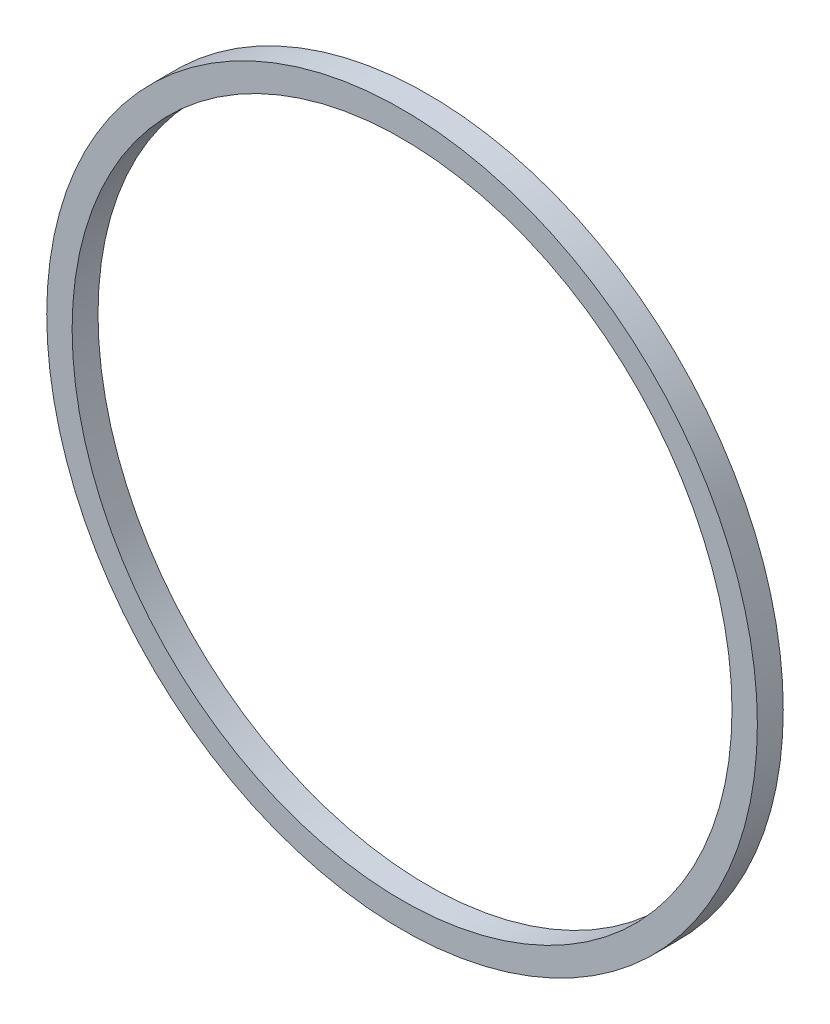
SolidWorks part; units mm, degrees
ref_plane "Front Plane" through (0, 0, 0) normal (0, 0, 1) x (1, 0, 0)
ref_plane "Top Plane" through (0, 0, 0) normal (0, 1, 0) x (1, 0, 0)
ref_plane "Right Plane" through (0, 0, 0) normal (1, 0, 0) x (0, 0, -1)
sketch "Sketch1" plane through (0, 0, 0) normal (0, 0, 1) x (1, 0, 0)
  circle A0 centre (0, 0) radius 70
  circle A1 centre (0, 0) radius 65
  dimension "D1" = 140
  dimension "130" = 130
extrude "Boss-Extrude1" add sketch "Sketch1" along normal blind 5.1
